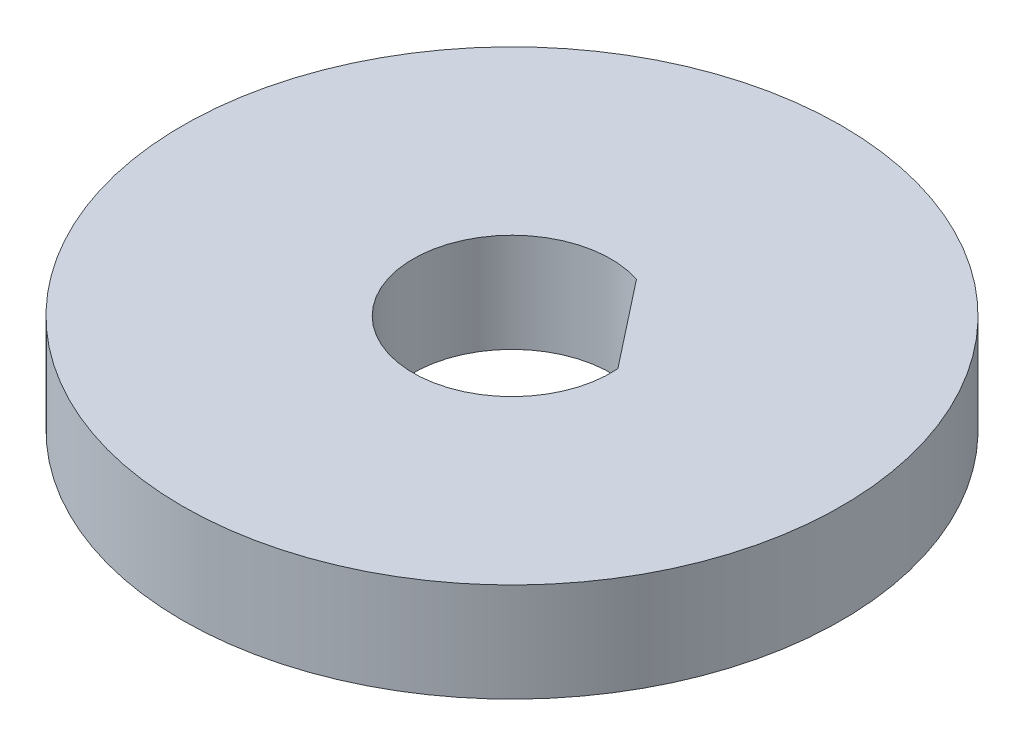
SolidWorks part; units mm, degrees
ref_plane "Front" through (0, 0, 0) normal (0, 0, 1) x (1, 0, 0)
ref_plane "Top" through (0, 0, 0) normal (0, 1, 0) x (1, 0, 0)
ref_plane "Right" through (0, 0, 0) normal (1, 0, 0) x (0, 0, -1)
sketch "Sketch1" plane through (0, 0, 0) normal (0, 1, 0) x (1, 0, 0)
  line L0 (1.989, 1.6309) -> (0.7808, 4.9427)
  circle A0 centre (0, 0) radius 10
  circle A1 centre (0, 0) radius 3
extrude "Boss-Extrude1" add sketch "Sketch1" along normal blind 3 contours A0 A1 | L0 A1
sketch "Sketch2" plane through (0, 3, 0) normal (0, 1, 0) x (1, 0, 0)
  line L0 (0.9226, 2.8546) -> (2.9919, 0.2201)
  circle A0 centre (0, 0) radius 3
  dimension "D1" = 3.35
extrude "Cut-Extrude1" cut sketch "Sketch2" against normal blind 3 contours L0 A0
